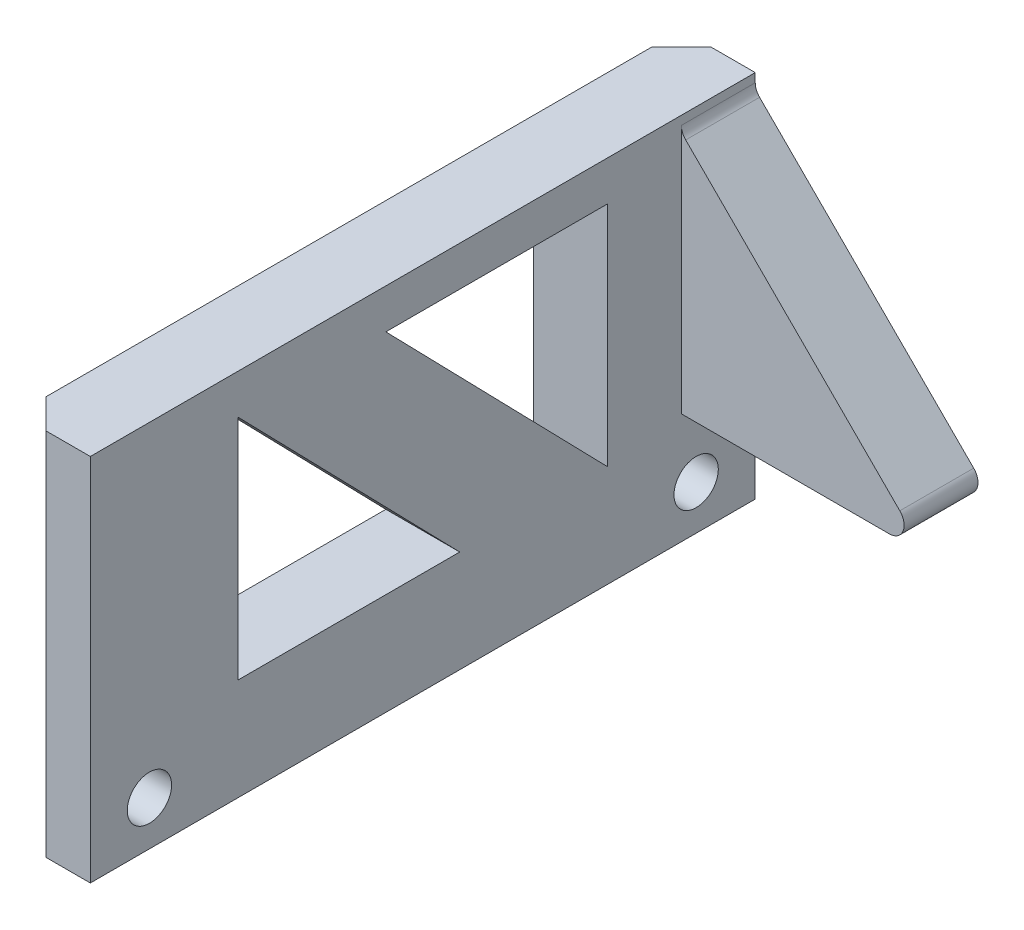
SolidWorks part; units mm, degrees
ref_plane "Front Plane" through (0, 0, 0) normal (0, 0, 1) x (1, 0, 0)
ref_plane "Top Plane" through (0, 0, 0) normal (0, 1, 0) x (1, 0, 0)
ref_plane "Right Plane" through (0, 0, 0) normal (1, 0, 0) x (0, 0, -1)
sketch "Sketch1" plane through (0, 0, 0) normal (1, 0, 0) x (0, 0, -1)
  line L1 (-22.5, 12.5) -> (22.5, 12.5)
  line L2 (-22.5, 12.5) -> (-22.5, -12.5)
  line L3 (-22.5, -12.5) -> (22.5, -12.5)
  line L4 (22.5, 12.5) -> (22.5, -12.5)
  line L5 (-22.5, 12.5) -> (22.5, -12.5) construction
  line L6 (-22.5, -12.5) -> (22.5, 12.5) construction
  point P0 (0, 0)
  dimension "D1" = 45
  dimension "D2" = 25
extrude "Boss-Extrude1" add sketch "Sketch1" along normal blind 5
sketch "Sketch2" plane through (5, 0, 0) normal (1, 0, 0) x (0, 0, -1)
  line L0 (-22.5, -12.5) -> (22.5, -12.5) construction
  circle A0 centre (-18.5, -9.5) radius 1.5
  circle A1 centre (18.5, -9.5) radius 1.5
  dimension "D2" = 3
  dimension "D3" = 3
  dimension "D1" = 37
  dimension "D4" = 18.5
  dimension "D5" = 3
  dimension "D6" = 3
extrude "Cut-Extrude1" cut sketch "Sketch2" against normal through all
sketch "Sketch3" plane through (5, 0, 0) normal (1, 0, 0) x (0, 0, -1)
  line L0 (-12.5, 9.8036) -> (-12.5, -5.5995)
  line L1 (-12.5, -5.5995) -> (2.5, -5.5995)
  line L2 (2.5, -5.5995) -> (-12.5, 9.8036)
  line L3 (-2.5, 9.8036) -> (12.5, 9.8036)
  line L4 (12.5, 9.8036) -> (12.5, -5.5995)
  line L6 (12.5, -5.5995) -> (-2.5, 9.8036)
  dimension "D1" = 15
  dimension "D2" = 15
extrude "Cut-Extrude2" cut sketch "Sketch3" against normal through all
chamfer "Chamfer2" distance 2 angle 45 2 edges at (0, 0, 22.5) (0, 0, -22.5)
sketch "Sketch4" plane through (0, 0, -22.5) normal (0, 0, -1) x (-1, 0, 0)
  line L0 (-5, -5) -> (-21.4903, -5)
  line L1 (-5, -12.5) -> (-5, 12.5) construction
  line L2 (-21.4903, -5) -> (-5, 11.4903)
  line L3 (-5, -12.5) -> (-2, -12.5) construction
  line L4 (-5, 11.4903) -> (-5, -5)
  dimension "D1" = 45
  dimension "D2" = 7.5
extrude "Boss-Extrude2" add sketch "Sketch4" against normal blind 5
fillet "Fillet1" radius 1 2 edges at (21.4903, -5, -20) (5, 11.4903, -20)
